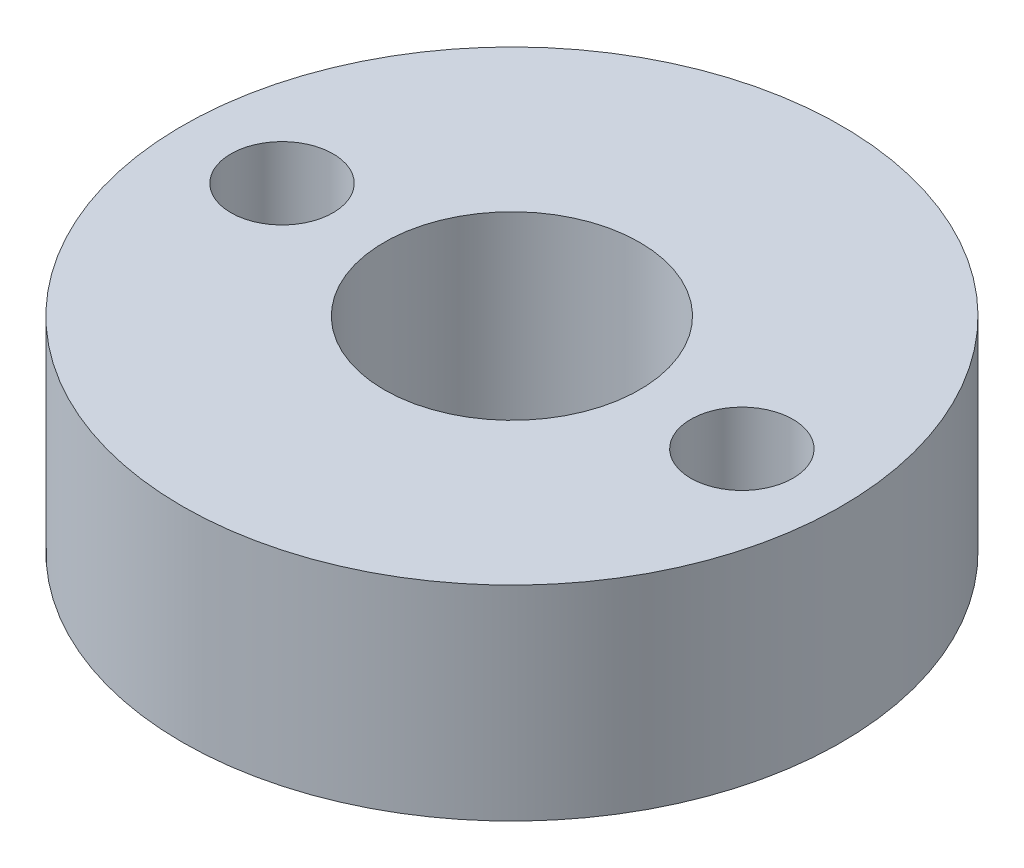
SolidWorks part; units mm, degrees
material "ABS PC"
ref_plane "Front Plane" through (0, 0, 0) normal (0, 0, 1) x (1, 0, 0)
ref_plane "Top Plane" through (0, 0, 0) normal (0, 1, 0) x (1, 0, 0)
ref_plane "Right Plane" through (0, 0, 0) normal (1, 0, 0) x (0, 0, -1)
sketch "Sketch1" plane through (0, 0, 0) normal (0, 1, 0) x (1, 0, 0)
  circle A0 centre (0, 0) radius 6.45
  dimension "D1" = 12.9
extrude "Boss-Extrude1" add sketch "Sketch1" along normal blind 4
sketch "Sketch2" plane through (0, 4, 0) normal (0, 1, 0) x (1, 0, 0)
  circle A0 centre (0, 0) radius 2.5
  circle A1 centre (4.5, 0) radius 1
  circle A2 centre (-4.5, 0) radius 1
  dimension "D1" = 5
  dimension "D2" = 9
  dimension "D3" = 4.5
  dimension "D4" = 2
  dimension "D5" = 2
extrude "Cut-Extrude1" cut sketch "Sketch2" against normal blind 4
